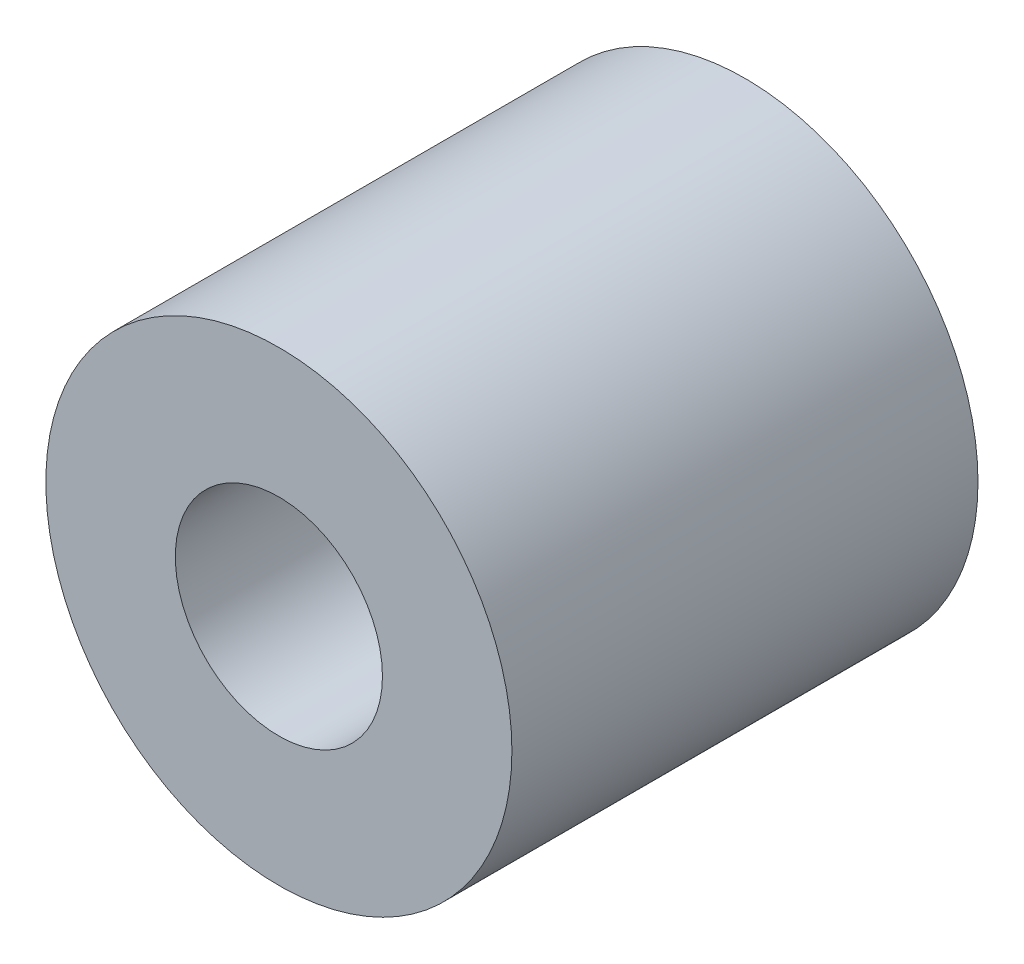
SolidWorks part; units mm, degrees
ref_plane "Ebene vorne" through (0, 0, 0) normal (0, 0, 1) x (1, 0, 0)
ref_plane "Ebene oben" through (0, 0, 0) normal (0, 1, 0) x (1, 0, 0)
ref_plane "Ebene rechts" through (0, 0, 0) normal (1, 0, 0) x (0, 0, -1)
sketch "Skizze1" plane through (0, 0, 0) normal (0, 0, 1) x (1, 0, 0)
  circle A0 centre (0, 0) radius 2
  circle A1 centre (0, 0) radius 4.5
  dimension "D1" = 4
  dimension "D2" = 9
extrude "Aufsatz-Linear austragen1" add sketch "Skizze1" along normal blind 9
